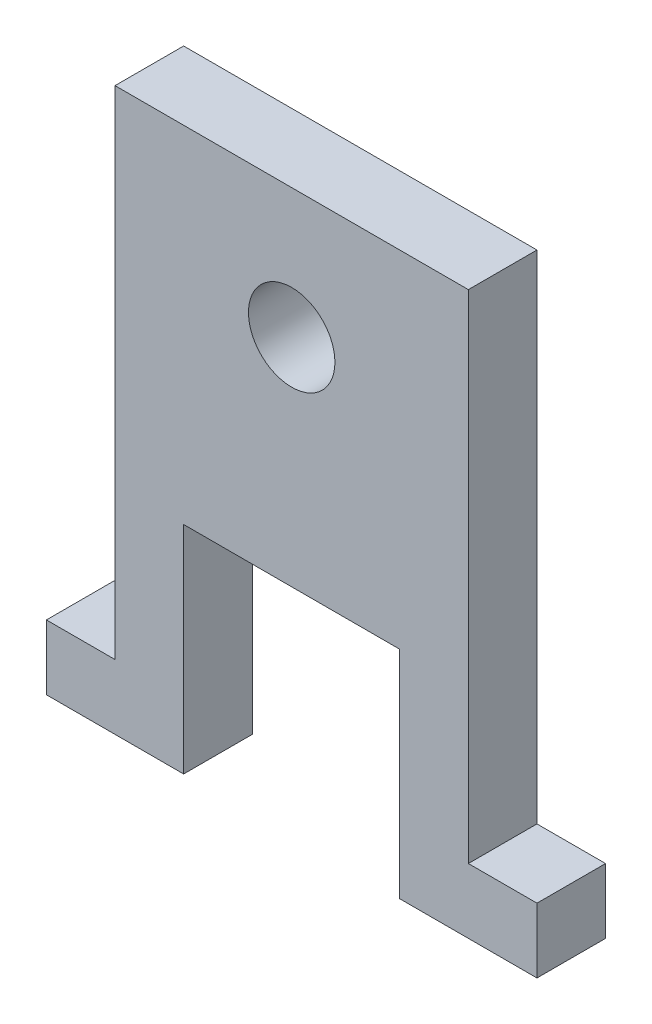
SolidWorks part; units mm, degrees
ref_plane "Front Plane" through (0, 0, 0) normal (0, 0, 1) x (1, 0, 0)
ref_plane "Top Plane" through (0, 0, 0) normal (0, 1, 0) x (1, 0, 0)
ref_plane "Right Plane" through (0, 0, 0) normal (1, 0, 0) x (0, 0, -1)
sketch "Sketch1" plane through (0, 0, 0) normal (0, 0, 1) x (1, 0, 0)
  line L0 (-10, -8.2) -> (-10, 11.8)
  line L1 (-10, 11.8) -> (10, 11.8)
  line L2 (10, 11.8) -> (10, -8.2)
  line L3 (-10, -8.2) -> (-22.7, -8.2)
  line L4 (-22.7, -8.2) -> (-22.7, -2.2)
  line L5 (-22.7, -2.2) -> (-16.35, -2.2)
  line L6 (-16.35, -2.2) -> (-16.35, 43.8)
  line L7 (-16.35, 43.8) -> (16.35, 43.8)
  line L8 (16.35, 43.8) -> (16.35, -2.2)
  line L9 (16.35, -2.2) -> (22.7, -2.2)
  line L10 (22.7, -2.2) -> (22.7, -8.2)
  line L11 (22.7, -8.2) -> (10, -8.2)
  circle A0 centre (0, 31.8) radius 4
  point P3 (0, 43.8)
  dimension "D10" = 8
  dimension "D1" = 20
  dimension "D2" = 20
  dimension "D3" = 20
  dimension "D4" = 12.7
  dimension "D5" = 12.7
  dimension "D6" = 6.35
  dimension "D7" = 6.35
  dimension "D8" = 32
  dimension "D9" = 20
extrude "Boss-Extrude1" add sketch "Sketch1" along normal blind 6.35
